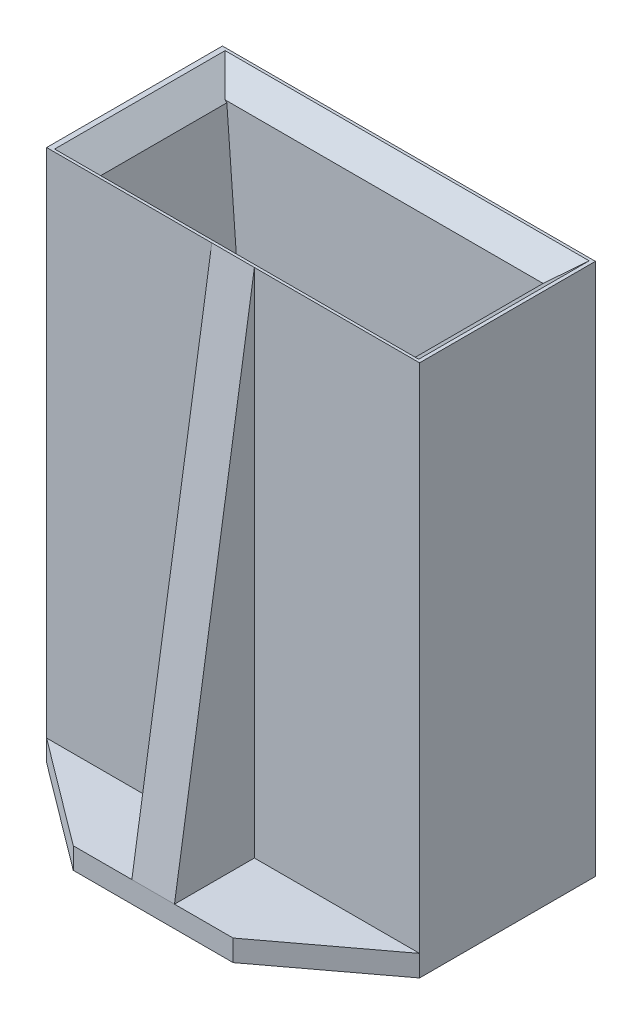
SolidWorks part; units mm, degrees
ref_plane "Front Plane" through (0, 0, 0) normal (0, 0, 1) x (1, 0, 0)
ref_plane "Top Plane" through (0, 0, 0) normal (0, 1, 0) x (1, 0, 0)
ref_plane "Right Plane" through (0, 0, 0) normal (1, 0, 0) x (0, 0, -1)
sketch "Sketch1" plane through (0, 0, 0) normal (0, 0, 1) x (1, 0, 0)
  line L1 (0, 0) -> (70, 0)
  line L2 (0, 0) -> (0, 100)
  line L3 (0, 100) -> (70, 100)
  line L4 (70, 0) -> (70, 100)
  dimension "D1" = 70
  dimension "D2" = 100
extrude "Boss-Extrude1" add sketch "Sketch1" along normal mid plane 33
sketch "Sketch2" plane through (0, 0, 0) normal (0, 0, 1) x (1, 0, 0)
  line L0 (70, 100) -> (0, 100) construction
  line L1 (5, 100) -> (65, 100)
  line L5 (35, 0) -> (35, 100) construction
  line L6 (0, 0) -> (70, 0) construction
  line L7 (5, 100) -> (12.4888, 0)
  line L8 (12.4888, 0) -> (57.5112, 0)
  line L9 (57.5112, 0) -> (65, 100)
  point P2 (35, 100)
  point P11 (0, 0)
  point P12 (35, 0)
  point P13 (12.4888, 0)
  dimension "D1" = 60
extrude "Cut-Extrude1" cut sketch "Sketch2" against normal mid plane 24
sketch "Sketch3" plane through (0, 0, 0) normal (0, -1, 0) x (1, 0, 0)
  line L0 (0, 16.5) -> (20, 31.5)
  line L1 (20, 31.5) -> (50, 31.5)
  line L2 (50, 31.5) -> (70, 16.5)
  line L3 (70, 16.5) -> (0, 16.5)
  line L4 (35, 31.5) -> (35, 16.5) construction
  line L5 (0, 0) -> (32.2231, 0) construction
  line L6 (50, -31.5) -> (70, -16.5)
  line L7 (20, -31.5) -> (50, -31.5)
  line L8 (0, -16.5) -> (20, -31.5)
  line L9 (70, -16.5) -> (0, -16.5)
  dimension "D1" = 15
  dimension "D2" = 30
extrude "Boss-Extrude2" add sketch "Sketch3" against normal blind 4
ref_plane "Plane1" through (35, 0, 0) normal (-1, 0, 0) x (0, 0, 1)
sketch "Sketch5" plane through (35, 0, 0) normal (-1, 0, 0) x (0, 0, 1)
  line L0 (-16.5, 100) -> (-31.5, 4)
  line L1 (-31.5, 4) -> (-16.5, 4)
  line L2 (-16.5, 4) -> (-16.5, 100)
  line L3 (0, 0) -> (0, 64.8712) construction
  line L4 (31.5, 4) -> (16.5, 4)
  line L5 (16.5, 100) -> (31.5, 4)
  line L6 (16.5, 4) -> (16.5, 100)
extrude "Boss-Extrude3" add sketch "Sketch5" along normal mid plane 8
chamfer "Chamfer1" distance 4 angle 45 4 edges at (5, 100, 0) (35, 100, 12) (65, 100, 0) (35, 100, -12)
